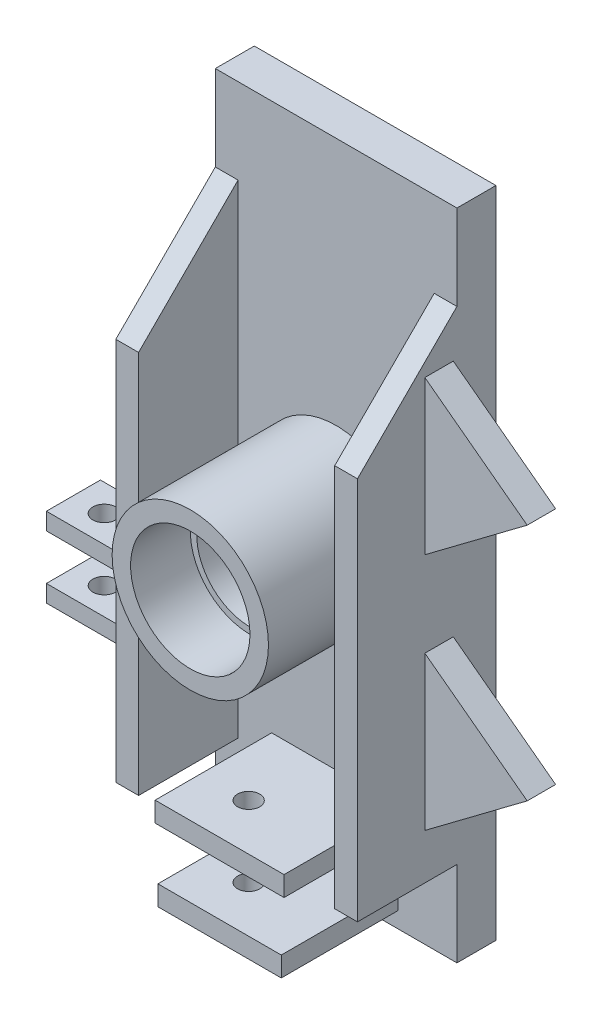
SolidWorks part; units mm, degrees
ref_plane "Front Plane" through (0, 0, 0) normal (0, 0, 1) x (1, 0, 0)
ref_plane "Top Plane" through (0, 0, 0) normal (0, 1, 0) x (1, 0, 0)
ref_plane "Right Plane" through (0, 0, 0) normal (1, 0, 0) x (0, 0, -1)
sketch "Sketch2" plane through (0, 0, 0) normal (0, 0, 1) x (1, 0, 0)
  circle A0 centre (0, 0) radius 27.5
  dimension "D1" = 55
extrude "Boss-Extrude1" add sketch "Sketch2" along normal blind 65.024
sketch "Sketch3" plane through (0, 0, 0) normal (0, 0, 1) x (1, 0, 0)
  line L1 (-42.5, -115) -> (42.5, -115)
  line L2 (-42.5, -115) -> (-42.5, 115)
  line L3 (-42.5, 115) -> (42.5, 115)
  line L4 (42.5, -115) -> (42.5, 115)
  line L5 (-42.5, -115) -> (42.5, 115) construction
  line L6 (-42.5, 115) -> (42.5, -115) construction
  point P0 (0, 0)
  dimension "D1" = 230
  dimension "D2" = 85
extrude "Boss-Extrude2" add sketch "Sketch3" along normal blind 13.716
sketch "Sketch4" plane through (0, 0, 13.716) normal (0, 0, 1) x (1, 0, 0)
  line L1 (-21.6971, -109.5) -> (21.6971, -109.5)
  line L2 (-21.6971, -109.5) -> (-21.6971, -102.5)
  line L3 (-21.6971, -102.5) -> (21.6971, -102.5)
  line L4 (21.6971, -109.5) -> (21.6971, -102.5)
  line L5 (-21.6971, -109.5) -> (21.6971, -102.5) construction
  line L6 (-21.6971, -102.5) -> (21.6971, -109.5) construction
  line L7 (-22.6805, -84.5) -> (22.6805, -84.5)
  line L8 (-22.6805, -84.5) -> (-22.6805, -77.5)
  line L9 (-22.6805, -77.5) -> (22.6805, -77.5)
  line L10 (22.6805, -84.5) -> (22.6805, -77.5)
  line L11 (-22.6805, -84.5) -> (22.6805, -77.5) construction
  line L12 (-22.6805, -77.5) -> (22.6805, -84.5) construction
  point P0 (0, -106)
  point P5 (0, -81)
  dimension "D1" = 81
  dimension "D2" = 7
  dimension "D3" = 25
extrude "Boss-Extrude3" add sketch "Sketch4" along normal blind 41 contours L3 L4 L1 L2 | L8 L7 L10 L9
sketch "Sketch7" plane through (0, 0, 65.024) normal (0, 0, 1) x (1, 0, 0)
  circle A0 centre (0, 0) radius 18.75
  dimension "D1" = 37.5
extrude "Cut-Extrude3" cut sketch "Sketch7" against normal up to surface (65.024 mm away) contours A0 up to face at (0, 0, 0)
sketch "Sketch5" plane through (0, 0, 65.024) normal (0, 0, 1) x (1, 0, 0)
  circle A0 centre (0, 0) radius 21
  dimension "D1" = 42
extrude "Cut-Extrude1" cut sketch "Sketch5" against normal blind 21 contours A0
sketch "Sketch6" plane through (0, 0, 0) normal (0, 0, -1) x (-1, 0, 0)
  circle A0 centre (0, 0) radius 23.5
  dimension "D1" = 47
extrude "Cut-Extrude2" cut sketch "Sketch6" against normal blind 15 contours A0
sketch "Sketch8" plane through (0, 0, 0) normal (0, 0, -1) x (-1, 0, 0)
  circle A0 centre (0, 0) radius 21
  dimension "D1" = 42
extrude "Cut-Extrude4" cut sketch "Sketch8" against normal blind 25 contours A0
sketch "Sketch10" plane through (0, 0, 13.716) normal (0, 0, 1) x (1, 0, 0)
  line L2 (0, 0) -> (0, 129.1129) construction
  line L5 (-42.5, -85) -> (-34.5, -85)
  line L11 (-42.5, 115) -> (-42.5, -115) construction
  line L12 (-42.5, -85) -> (-42.5, 85)
  line L13 (-42.5, 85) -> (-34.5, 85)
  line L14 (-34.5, -85) -> (-34.5, 85)
  line L15 (-42.5, -85) -> (-34.5, 85) construction
  line L16 (-42.5, 85) -> (-34.5, -85) construction
  line L17 (42.5, -85) -> (34.5, 85) construction
  line L18 (42.5, 85) -> (34.5, -85) construction
  line L19 (42.5, -85) -> (34.5, -85)
  line L20 (42.5, -85) -> (42.5, 85)
  line L21 (42.5, 85) -> (34.5, 85)
  line L22 (34.5, -85) -> (34.5, 85)
  point P0 (-38.5, 0)
  point P7 (38.5, 0)
  point P12 (-29.5514, -14.568)
  point P13 (-35.9182, -41.0823)
  point P14 (-196.4312, 98.3572)
  point P15 (-25.3027, 71.4739)
  point P16 (-32.4596, 0)
  point P17 (-29.5291, 68.0371)
  dimension "D1" = 8
  dimension "D2" = 85
extrude "Boss-Extrude4" add sketch "Sketch10" along normal blind 35
sketch "Sketch11" plane through (-42.5, 0, 0) normal (-1, 0, 0) x (0, 0, 1)
  line L0 (13.716, 85) -> (48.716, 50)
  line L3 (48.716, 50) -> (48.716, 85)
  line L4 (48.716, 85) -> (13.716, 85)
  line L5 (13.716, 115) -> (13.716, 85) construction
  point P0 (13.716, 71.2254)
  dimension "D1" = 35
extrude "Cut-Extrude5" cut sketch "Sketch11" against normal up to surface (85 mm away) up to face at (42.5, 0, 19.037)
ref_plane "Plane2" through (0, 0, 45) normal (0, 0, -1) x (-1, 0, 0)
sketch "Sketch12" plane through (0, 0, 45) normal (0, 0, -1) x (-1, 0, 0)
  circle A0 centre (0, 0) radius 27.5 construction
  circle A1 centre (0, 0) radius 27.5
  point P0 (0, 95)
  dimension "D1" = 95
ref_point "Point1"
ref_plane "Plane3" through (0, 0, 38.35) normal (0, 0, -1) x (-1, 0, 0)
sketch "Sketch13" plane through (0, 0, 38.35) normal (0, 0, -1) x (-1, 0, 0)
  point P0 (6.1439, -95.5)
  point P1 (0, 95)
  dimension "D1" = 190.5
ref_point "Point2"
sketch "Sketch14" plane through (0, -77.5, 0) normal (0, 1, 0) x (1, 0, 0)
  circle A0 centre (-6.1439, -38.35) radius 3.8982
  point P0 (-6.1439, -38.35)
extrude "Cut-Extrude6" cut sketch "Sketch14" against normal up to surface (32 mm away) up to face at (0, -109.5, 34.216)
sketch "Sketch16" plane through (0, 0, 0) normal (0, 0, 1) x (1, 0, 0)
  line L0 (42.5, -85) -> (42.5, 50) construction
  line L1 (42.5, -85) -> (42.5, 69) construction
  line L2 (42.5, 69) -> (78.5, 42)
  line L3 (78.5, 42) -> (42.5, 15)
  line L4 (0, 0) -> (98.8403, 0) construction
  line L5 (78.5, -42) -> (42.5, -15)
  line L6 (42.5, -69) -> (78.5, -42)
  line L7 (42.5, 15) -> (42.5, 69)
  line L8 (42.5, -15) -> (42.5, -69)
  line L9 (78.5, 42) -> (42.5, 42) construction
  line L10 (78.5, -42) -> (42.5, -42) construction
  point P7 (60.5, 42)
  point P14 (60.5, -42)
  dimension "D1" = 15
  dimension "D2" = 45
  dimension "D3" = 84
extrude "Boss-Extrude5" add sketch "Sketch16" along normal blind 10 from offset 15 contours L5 L8 L6 | L2 L3 L7
ref_plane "Plane4" through (0, 0, 25.65) normal (0, 0, -1) x (-1, 0, 0)
sketch "Sketch20" plane through (0, 0, 25.65) normal (0, 0, -1) x (-1, 0, 0)
  point P0 (69.6439, -42.16)
  dimension "D1" = 53.34
  dimension "D2" = 63.5
ref_point "Point3"
sketch "Sketch21" plane through (-42.5, 0, 0) normal (-1, 0, 0) x (0, 0, 1)
  line L0 (25.65, -31.16) -> (25.65, -42.16) construction
  line L1 (16.15, -34.16) -> (35.15, -34.16)
  line L2 (16.15, -34.16) -> (16.15, -28.16)
  line L3 (16.15, -28.16) -> (35.15, -28.16)
  line L4 (35.15, -34.16) -> (35.15, -28.16)
  line L5 (16.15, -34.16) -> (35.15, -28.16) construction
  line L6 (16.15, -28.16) -> (35.15, -34.16) construction
  line L7 (16.15, -56.16) -> (35.15, -56.16)
  line L8 (16.15, -56.16) -> (16.15, -50.16)
  line L9 (16.15, -50.16) -> (35.15, -50.16)
  line L10 (35.15, -56.16) -> (35.15, -50.16)
  line L11 (16.15, -56.16) -> (35.15, -50.16) construction
  line L12 (16.15, -50.16) -> (35.15, -56.16) construction
  line L13 (25.65, -42.16) -> (25.65, -53.16) construction
  point P0 (25.65, -31.16)
  point P5 (25.65, -53.16)
  point P10 (25.65, -42.16)
  dimension "D1" = 11
  dimension "D2" = 6
  dimension "D3" = 19
extrude "Boss-Extrude6" add sketch "Sketch21" along normal blind 38 contours L7 L10 L9 L8 | L3 L4 L1 L2
sketch "Sketch22" plane through (0, -28.16, 0) normal (0, 1, 0) x (1, 0, 0)
  circle A0 centre (-69.6439, -25.65) radius 4
  point P2 (-69.6439, -25.65)
  point P4 (-69.6439, -25.65)
  dimension "D1" = 8
extrude "Cut-Extrude7" cut sketch "Sketch22" against normal up to surface (28 mm away) contours A0 up to face at (-61.5, -56.16, 25.65)
